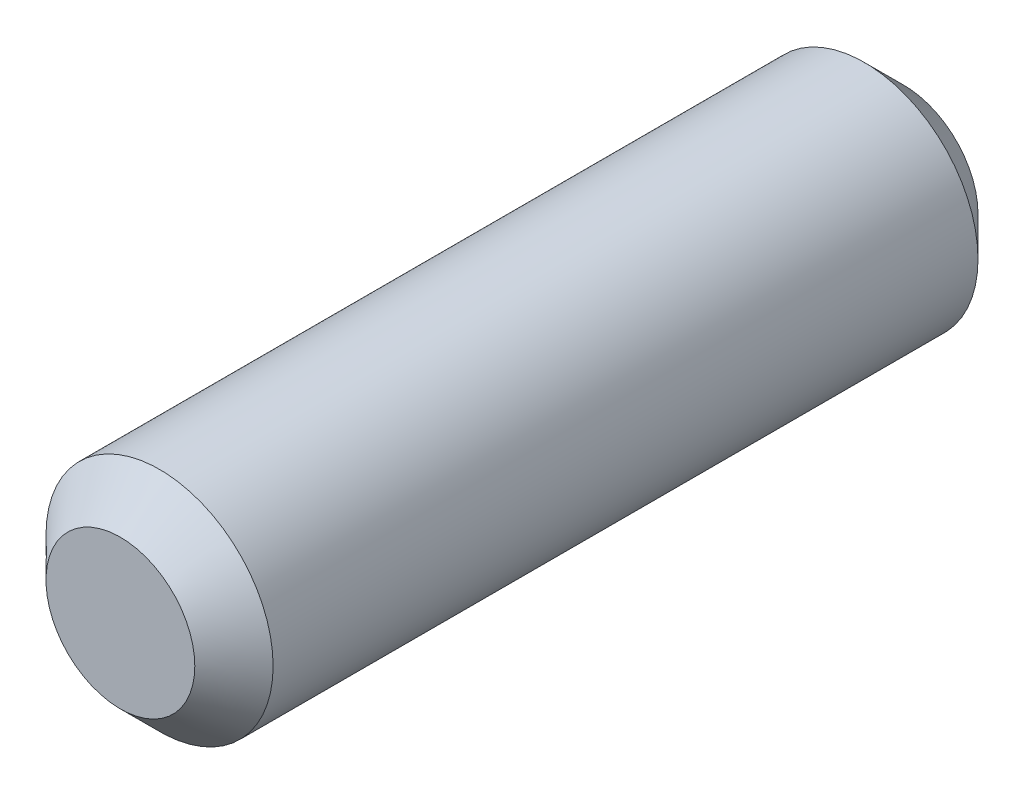
SolidWorks part; units mm, degrees
ref_plane "Plan de face" through (0, 0, 0) normal (0, 0, 1) x (1, 0, 0)
ref_plane "Plan de dessus" through (0, 0, 0) normal (0, 1, 0) x (1, 0, 0)
ref_plane "Plan de droite" through (0, 0, 0) normal (1, 0, 0) x (0, 0, -1)
sketch "Esquisse1" plane through (0, 0, 0) normal (0, 0, 1) x (1, 0, 0)
  circle A0 centre (0, 0) radius 1.45
  dimension "D1" = 2.9
extrude "Boss.-Extru.1" add sketch "Esquisse1" along normal blind 10
chamfer "Chanfrein1" distance 0.5 angle 45 2 edges at (1.45, 0, 10) (1.45, 0, 0)
